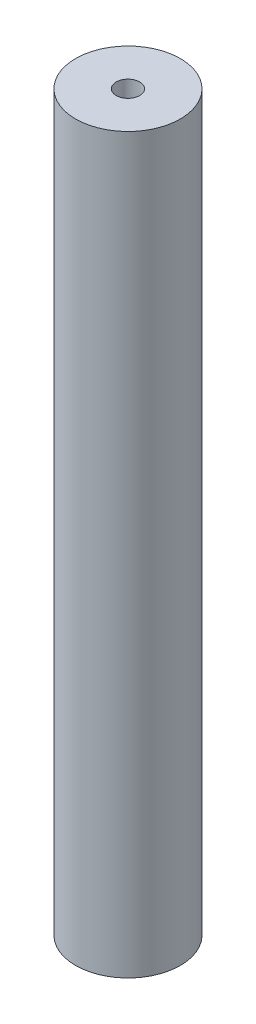
SolidWorks part; units mm, degrees
ref_plane "Спереди" through (0, 0, 0) normal (0, 0, 1) x (1, 0, 0)
ref_plane "Сверху" through (0, 0, 0) normal (0, 1, 0) x (1, 0, 0)
ref_plane "Справа" through (0, 0, 0) normal (1, 0, 0) x (0, 0, -1)
other "Configuration Table"
sketch "Эскиз1" plane through (0, 0, 0) normal (0, 1, 0) x (1, 0, 0)
  circle A0 centre (0, 0) radius 10
  dimension "D1" = 20
extrude "Бобышка-Вытянуть1" add sketch "Эскиз1" along normal blind 70
hole_wizard "Отверстие с зазором M41" positions "Эскиз2" profile "Эскиз4" hole size "M4" standard "AS"
sketch "Эскиз2" plane through (0, 70, 0) normal (0, 1, 0) x (1, 0, 0)
  point P0 (0, 0)
sketch "Эскиз4" plane through (0, 70, 0) normal (1, 0, 0) x (0, 0, 1)
  line L0 (0, 0) -> (0, 17.3519)
  line L1 (0, 17.3519) -> (2.25, 16)
  line L2 (2.25, 16) -> (2.25, 0)
  line L5 (2.25, 0) -> (0, 0)
  line L10 (0, 17.3519) -> (-2.25, 16) construction
  line L11 (0, -6.35) -> (0, 107.95) construction
  dimension "Диаметр отверстия" = 4.5
  dimension "Глубина отверстия" = 16
  dimension "Угол заточки сверла" = 118
mirror "Зеркальное отражение1" about plane through (0, 0, 0) normal (0, 1, 0) of "Бобышка-Вытянуть1", "Отверстие с зазором M41"
